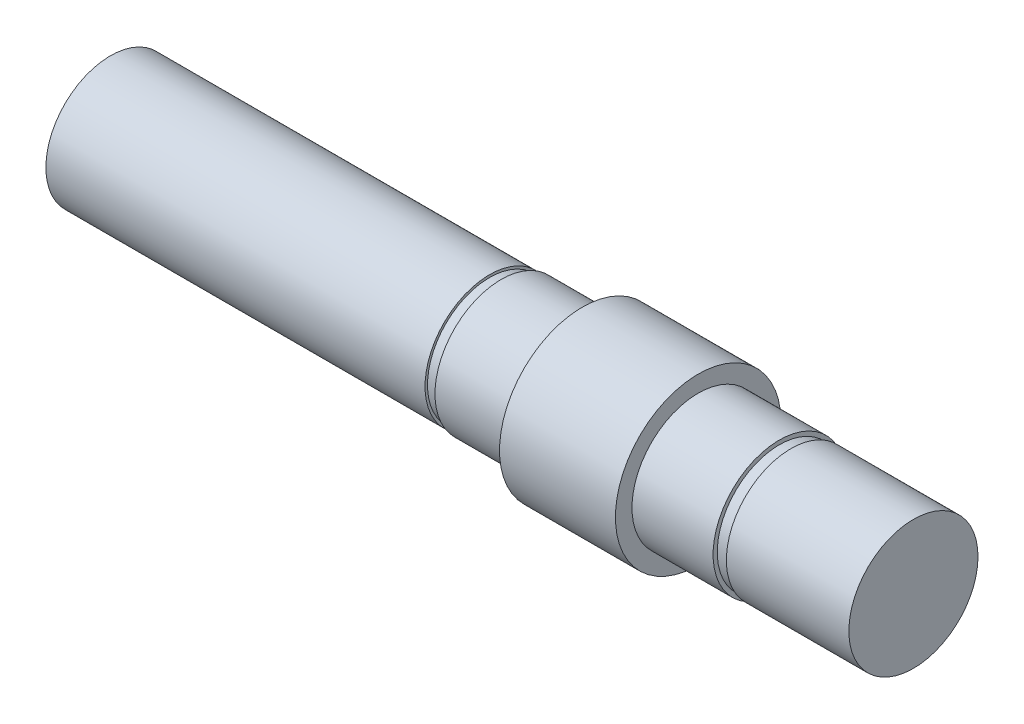
SolidWorks part; units mm, degrees
material "5052-H32"
ref_plane "Front Plane" through (0, 0, 0) normal (0, 0, 1) x (1, 0, 0)
ref_plane "Top Plane" through (0, 0, 0) normal (0, 1, 0) x (1, 0, 0)
ref_plane "Right Plane" through (0, 0, 0) normal (1, 0, 0) x (0, 0, -1)
sketch "Sketch2" plane through (0, 0, 0) normal (0, 0, 1) x (1, 0, 0)
  line L15 (128, -117.2) -> (123.1, -117.2) construction
  line L17 (123.1, -117.2) -> (123.1, -117.45) construction
  line L18 (123.1, -117.45) -> (122.4, -117.45) construction
  line L19 (122.4, -117.45) -> (122.4, -117.3) construction
  line L20 (122.4, -117.3) -> (115, -117.3) construction
  line L24 (148, -121.2) -> (115, -121.2) construction
  line L25 (148, -117.3) -> (148, -121.2) construction
  line L26 (140.6, -117.3) -> (148, -117.3) construction
  line L27 (140.6, -117.45) -> (140.6, -117.3) construction
  line L28 (139.9, -117.45) -> (140.6, -117.45) construction
  line L29 (139.9, -117.2) -> (139.9, -117.45) construction
  line L30 (135, -117.2) -> (139.9, -117.2) construction
  line L31 (135, -116.2) -> (135, -117.2) construction
  line L32 (135, -116.2) -> (128, -116.2) construction
  line L33 (128, -116.2) -> (128, -117.2) construction
  line L34 (128, -117.2) -> (123.1, -117.2)
  line L35 (123.1, -117.2) -> (123.1, -117.45)
  line L36 (123.1, -117.45) -> (122.4, -117.45)
  line L37 (122.4, -117.45) -> (122.4, -117.3)
  line L38 (122.4, -117.3) -> (115, -117.3)
  line L42 (148, -121.2) -> (115, -121.2)
  line L43 (148, -117.3) -> (148, -121.2)
  line L44 (140.6, -117.3) -> (148, -117.3)
  line L45 (140.6, -117.45) -> (140.6, -117.3)
  line L46 (139.9, -117.45) -> (140.6, -117.45)
  line L47 (139.9, -117.2) -> (139.9, -117.45)
  line L48 (135, -117.2) -> (139.9, -117.2)
  line L49 (135, -116.2) -> (135, -117.2)
  line L50 (135, -116.2) -> (128, -116.2)
  line L51 (128, -116.2) -> (128, -117.2)
  line L52 (123, 0) -> (123, -117.45) construction
  line L53 (123, -117.45) -> (123, 0) construction
  line L54 (140, -117.45) -> (140, -100.6386) construction
  line L55 (108.5, -121.2) -> (115, -121.2) construction
  line L56 (108.5, -121.2) -> (99.5, -121.2) construction
  line L57 (99.5, -117.3) -> (99.5, -121.2) construction
  line L58 (115, -117.3) -> (99.5, -117.3) construction
  line L59 (108.5, -121.2) -> (115, -121.2)
  line L60 (108.5, -121.2) -> (99.5, -121.2)
  line L61 (99.5, -117.3) -> (99.5, -121.2)
  line L62 (115, -117.3) -> (99.5, -117.3)
  dimension "D1" = 0.1
  dimension "D2" = 0.1
revolve "Revolve1" add sketch "Sketch2" angle 360 about L42
sketch "Sketch3" [suppressed] plane through (0, 0, 0) normal (0, 0, 1) x (1, 0, 0)
  line L0 (148, -119.2) -> (160, -119.2)
  line L1 (160, -119.2) -> (160, -121.2)
  line L2 (160, -121.2) -> (148, -121.2)
  line L3 (148, -121.2) -> (148, -119.2)
revolve "Revolve2" [suppressed] add sketch "Sketch3" angle 360 about L2
equation "\"D2@Sketch2\"=\"D1@Sketch2\""
